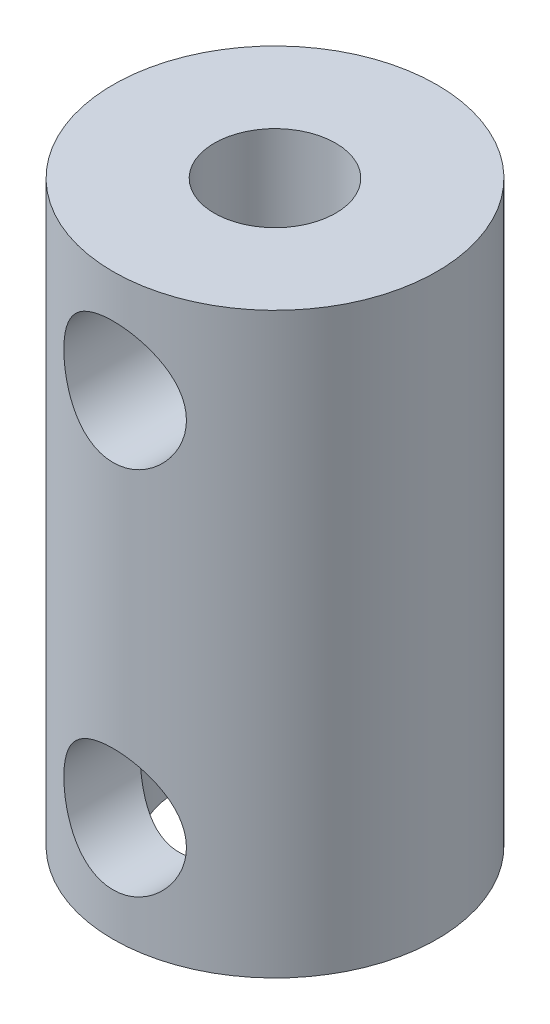
SolidWorks part; units mm, degrees
ref_plane "Front Plane" through (0, 0, 0) normal (0, 0, 1) x (1, 0, 0)
ref_plane "Top Plane" through (0, 0, 0) normal (0, 1, 0) x (1, 0, 0)
ref_plane "Right Plane" through (0, 0, 0) normal (1, 0, 0) x (0, 0, -1)
sketch "Sketch1" plane through (0, 0, 0) normal (0, 0, 1) x (1, 0, 0)
  line L0 (5.334, 19.05) -> (0, 19.05)
  line L1 (0, 19.05) -> (0, 0)
  line L2 (0, 0) -> (5.334, 0)
  line L3 (5.334, 0) -> (5.334, 19.05)
  line L4 (0, 19.05) -> (0, 0) construction
revolve "Revolve1" add sketch "Sketch1" angle 360 about L4
hole_wizard "CSK for #6 Flat Head Machine Screw (100)1" positions "Sketch3" profile "Sketch2" countersink size "#6" standard "ANSI Inch"
sketch "Sketch3" plane through (0, 0, 0) normal (0, -1, 0) x (-1, 0, 0)
  point P0 (0, 0)
sketch "Sketch2" plane through (0, 0, 0) normal (1, 0, 0) x (0, 0, -1)
  line L0 (0, 0) -> (0, 19.05)
  line L1 (0, 19.05) -> (2, 19.05)
  line L2 (2, 19.05) -> (2, 10.231)
  line L3 (2, 10.231) -> (3.175, 9.525)
  line L4 (3.175, 9.525) -> (3.175, 0)
  line L6 (3.175, 0) -> (0, 0)
  line L7 (-2, 10.231) -> (-3.175, 9.525) construction
  line L11 (0, -6.35) -> (0, 107.95) construction
  dimension "Thru Hole Dia." = 4
  dimension "Thru Hole Depth" = 19.05
  dimension "C'Sink Dia." = 6.35
  dimension "C'Sink Angle" = 118
  dimension "Head Clearance" = 9.525
hole_wizard "#21 (0.159) Diameter Hole1" positions "3DSketch1" profile "Sketch4" hole size "#21" standard "ANSI Inch"
sketch3d "3DSketch1"
  point P0 (0, 15.621, 5.334)
sketch "Sketch4" plane through (0, 15.621, 5.334) normal (1, 0, 0) x (0, -1, 0)
  line L0 (0, 0) -> (0, 5.334)
  line L1 (0, 5.334) -> (2.0193, 5.334)
  line L2 (2.0193, 5.334) -> (2.0193, 0)
  line L5 (2.0193, 0) -> (0, 0)
  line L10 (0, 5.334) -> (-2.0193, 5.334) construction
  line L11 (0, -6.35) -> (0, 107.95) construction
  dimension "Hole Dia." = 4.0386
  dimension "Hole Depth" = 5.334
  dimension "Drill Angle" = 180
hole_wizard "#21 (0.159) Diameter Hole2" positions "3DSketch2" profile "Sketch5" hole size "#21" standard "ANSI Inch"
sketch3d "3DSketch2"
  point P0 (0, 3.429, 5.334)
sketch "Sketch5" plane through (0, 3.429, 5.334) normal (1, 0, 0) x (0, -1, 0)
  line L0 (0, 0) -> (0, 2.159)
  line L1 (0, 2.159) -> (2.0193, 2.159)
  line L2 (2.0193, 2.159) -> (2.0193, 0)
  line L5 (2.0193, 0) -> (0, 0)
  line L11 (0, -6.35) -> (0, 107.95) construction
  dimension "Thru Hole Dia." = 4.0386
  dimension "Thru Hole Depth" = 2.159
